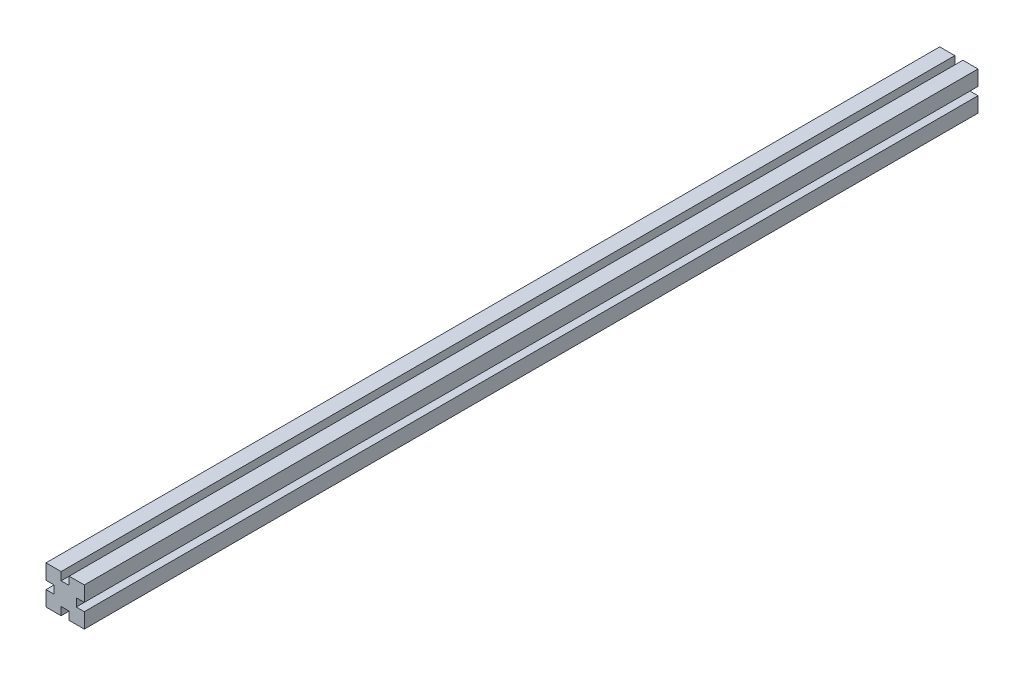
SolidWorks part; units mm, degrees
ref_plane "Front Plane" through (0, 0, 0) normal (0, 0, 1) x (1, 0, 0)
ref_plane "Top Plane" through (0, 0, 0) normal (0, 1, 0) x (1, 0, 0)
ref_plane "Right Plane" through (0, 0, 0) normal (1, 0, 0) x (0, 0, -1)
sketch "Sketch1" plane through (0, 0, 0) normal (0, 0, 1) x (1, 0, 0)
  line L0 (-19.05, -19.05) -> (-4, -19.05)
  line L1 (-4, -19.05) -> (-4, -11.05)
  line L2 (-4, -11.05) -> (4, -11.05)
  line L3 (4, -11.05) -> (4, -19.05)
  line L4 (4, -19.05) -> (19.05, -19.05)
  line L5 (19.05, -19.05) -> (19.05, -4)
  line L6 (19.05, -4) -> (11.05, -4)
  line L7 (11.05, -4) -> (11.05, 4)
  line L8 (11.05, 4) -> (19.05, 4)
  line L9 (19.05, 4) -> (19.05, 19.05)
  line L10 (19.05, 19.05) -> (4, 19.05)
  line L11 (4, 19.05) -> (4, 11.05)
  line L12 (4, 11.05) -> (-4, 11.05)
  line L13 (-4, 11.05) -> (-4, 19.05)
  line L14 (-4, 19.05) -> (-19.05, 19.05)
  line L15 (-19.05, 19.05) -> (-19.05, 4)
  line L16 (-19.05, 4) -> (-11.05, 4)
  line L17 (-11.05, 4) -> (-11.05, -4)
  line L18 (-11.05, -4) -> (-19.05, -4)
  line L19 (-19.05, -4) -> (-19.05, -19.05)
extrude "Profile" add sketch "Sketch1" along normal blind 889
equation "\"length\" = 889.0mm"
equation "\"D1@Profile\" = \"length\""
